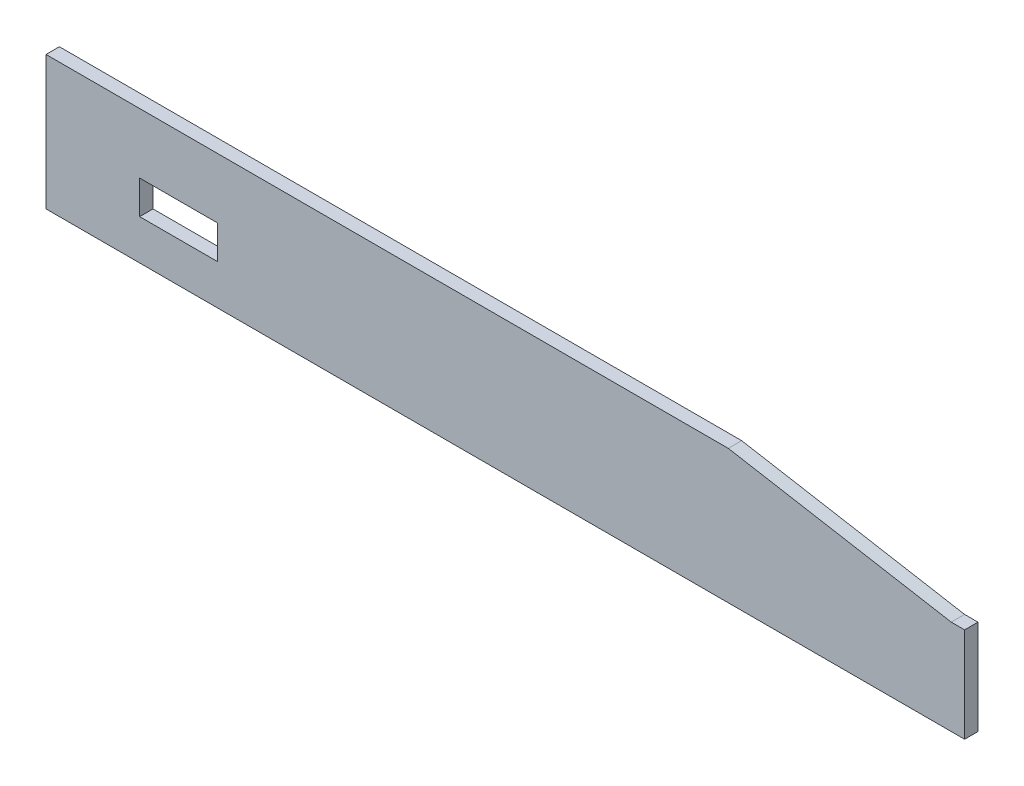
SolidWorks part; units mm, degrees
material "CA"
ref_plane "Front Plane" through (0, 0, 0) normal (0, 0, 1) x (1, 0, 0)
ref_plane "Top Plane" through (0, 0, 0) normal (0, 1, 0) x (1, 0, 0)
ref_plane "Right Plane" through (0, 0, 0) normal (1, 0, 0) x (0, 0, -1)
sketch "Sketch1" plane through (0, 0, 0) normal (0, 0, 1) x (1, 0, 0)
  line L0 (-153, 30) -> (-153, -30)
  line L1 (-153, -30) -> (259, -30)
  line L3 (153, 30) -> (-153, 30)
  line L4 (-76, 3) -> (-111, 3)
  line L5 (259, -30) -> (259, 12.5)
  line L6 (259, 12.5) -> (253, 12.5)
  line L7 (253, 12.5) -> (153, 30)
  line L8 (-76, 3) -> (-76, -12)
  line L9 (-76, -12) -> (-111, -12)
  line L10 (-111, 3) -> (-111, -12)
  point P10 (-153, 0)
  point P12 (0, 30)
  dimension "D1" = 306
  dimension "D2" = 60
  dimension "D3" = 42.5
  dimension "D4" = 412
  dimension "D5" = 101.5197
  dimension "D6" = 35
  dimension "D7" = 15
  dimension "D8" = 18
  dimension "D9" = 42
extrude "Boss-Extrude1" add sketch "Sketch1" along normal blind 6
